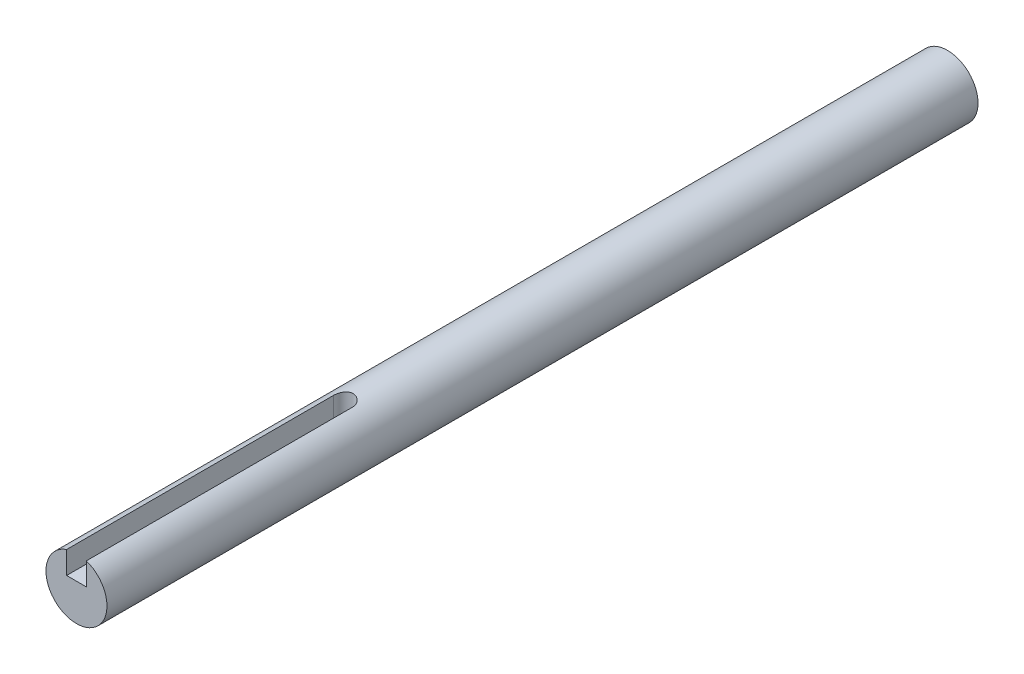
SolidWorks part; units mm, degrees
ref_plane "Front Plane" through (0, 0, 0) normal (0, 0, 1) x (1, 0, 0)
ref_plane "Top Plane" through (0, 0, 0) normal (0, 1, 0) x (1, 0, 0)
ref_plane "Right Plane" through (0, 0, 0) normal (1, 0, 0) x (0, 0, -1)
sketch "Sketch1" plane through (0, 0, 0) normal (0, 0, 1) x (1, 0, 0)
  circle A0 centre (0, 0) radius 4
extrude "Boss-Extrude1" add sketch "Sketch1" along normal blind 114.3
sketch "Sketch2" plane through (0, 0, 114.3) normal (0, 0, 1) x (1, 0, 0)
  line L2 (-1.2954, 3.4214) -> (-1.2954, 6.4214)
  line L3 (-1.2954, 6.4214) -> (1.2954, 6.4214)
  line L4 (1.2954, 6.4214) -> (1.2954, 3.4214)
  line L5 (0, 0.825) -> (-1.2954, 0.825)
  line L6 (-1.2954, 0.825) -> (-1.2954, 3.4214)
  line L7 (0, 0.825) -> (1.2954, 0.825)
  line L8 (1.2954, 0.825) -> (1.2954, 3.4214)
extrude "Boss-Extrude2" add sketch "Sketch2" against normal blind 35
sketch "Sketch3" plane through (0, 6.4214, 0) normal (0, 1, 0) x (1, 0, 0)
  line L2 (-1.2954, -79.3) -> (-1.2954, -114.3)
  line L3 (-1.2954, -114.3) -> (1.2954, -114.3)
  line L4 (1.2954, -79.3) -> (1.2954, -114.3)
  arc A0 (-1.2954, -79.3) -> (1.2954, -79.3) centre (0, -79.3) cw
extrude "Cut-Extrude1" cut sketch "Sketch3" against normal blind 5.5964
sketch "Sketch5" plane through (0, 0.825, 0) normal (0, 1, 0) x (1, 0, 0)
